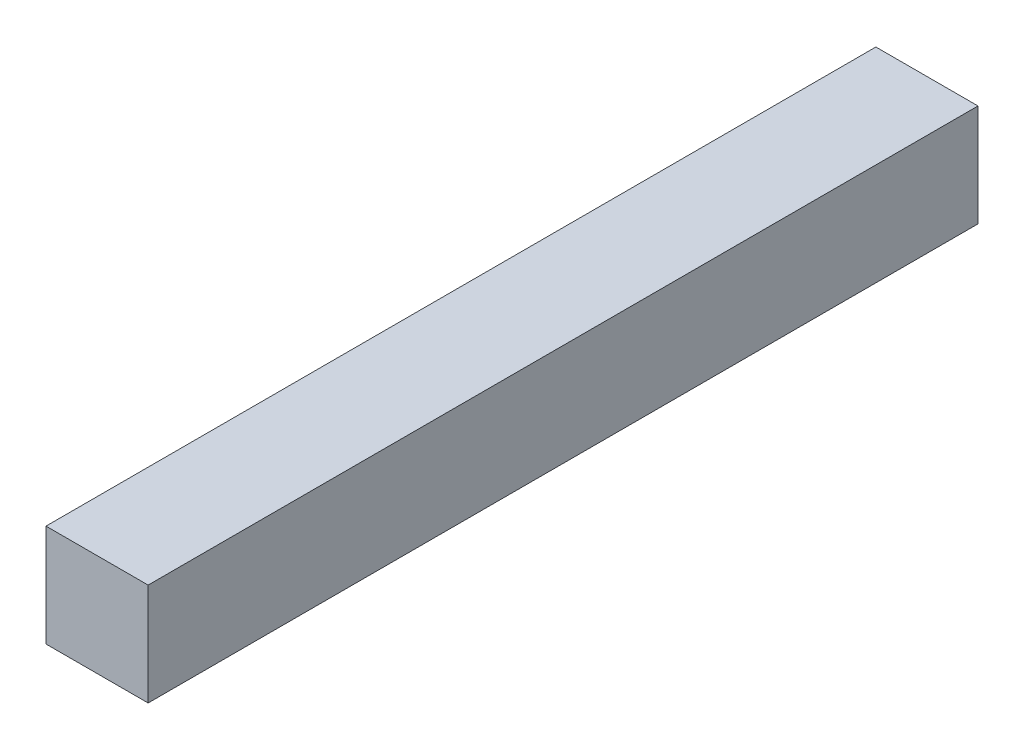
SolidWorks part; units mm, degrees
ref_plane "Přední rovina" through (0, 0, 0) normal (0, 0, 1) x (1, 0, 0)
ref_plane "Horní rovina" through (0, 0, 0) normal (0, 1, 0) x (1, 0, 0)
ref_plane "Pravá rovina" through (0, 0, 0) normal (1, 0, 0) x (0, 0, -1)
sketch "Skica1" plane through (0, 0, 0) normal (0, 0, 1) x (1, 0, 0)
  line L1 (0, 0) -> (0.8, 0)
  line L2 (0, 0) -> (0, 0.8)
  line L3 (0, 0.8) -> (0.8, 0.8)
  line L4 (0.8, 0) -> (0.8, 0.8)
  dimension "D1" = 0.8
  dimension "D2" = 0.8
extrude "Přidat vysunutím1" add sketch "Skica1" along normal blind 17
sketch "Skica2" plane through (0, 0, 0) normal (0, 0, -1) x (-1, 0, 0)
  line L1 (0, 0) -> (-0.8, 0)
  line L2 (0, 0) -> (0, 0.8)
  line L3 (0, 0.8) -> (-0.8, 0.8)
  line L4 (-0.8, 0) -> (-0.8, 0.8)
extrude "Odebrat vysunutím2" cut sketch "Skica2" against normal blind 3
sketch "Skica3" plane through (0, 0, 17) normal (0, 0, 1) x (1, 0, 0)
  line L1 (0, 0) -> (0.8, 0)
  line L2 (0, 0) -> (0, 0.8)
  line L3 (0, 0.8) -> (0.8, 0.8)
  line L4 (0.8, 0) -> (0.8, 0.8)
extrude "Odebrat vysunutím3" cut sketch "Skica3" against normal blind 7.5
